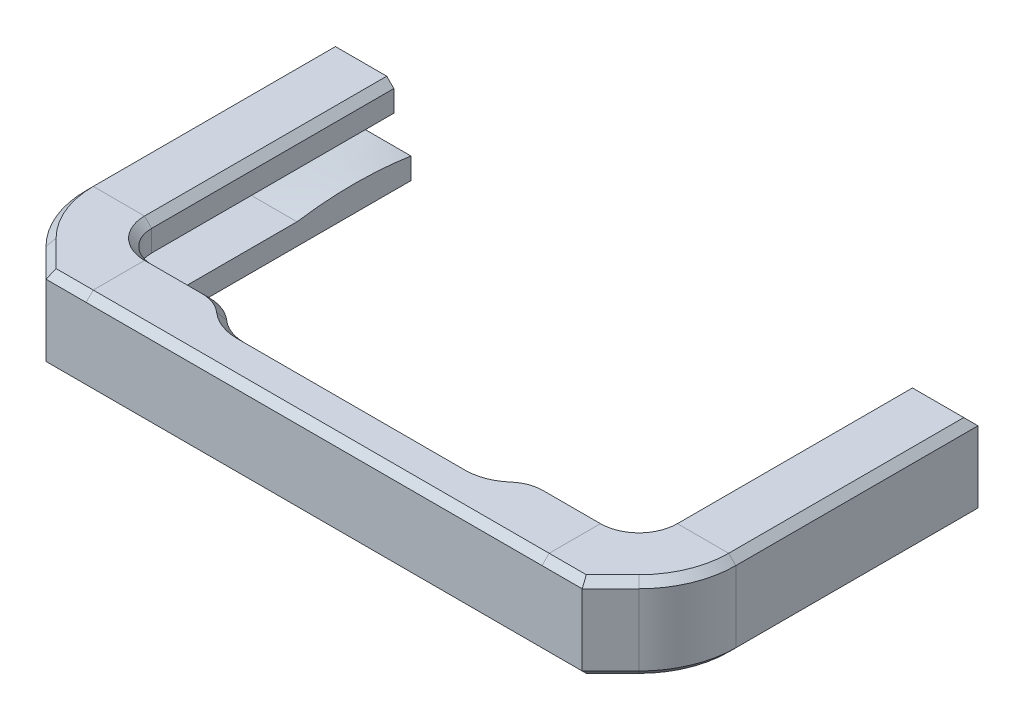
SolidWorks part; units mm, degrees
ref_plane "Front Plane" through (0, 0, 0) normal (0, 0, 1) x (1, 0, 0)
ref_plane "Top Plane" through (0, 0, 0) normal (0, 1, 0) x (1, 0, 0)
ref_plane "Right Plane" through (0, 0, 0) normal (1, 0, 0) x (0, 0, -1)
sketch "Sketch1" plane through (0, 0, 0) normal (0, 1, 0) x (1, 0, 0)
  line L0 (-16, 0) -> (16, 0)
  line L5 (-20, 4) -> (-20, 21)
  line L6 (20, 4) -> (20, 21)
  line L7 (-20, 21) -> (20, 21) construction
  arc A0 (16, 0) -> (20, 4) centre (16, 4) ccw
  arc A1 (-16, 0) -> (-20, 4) centre (-16, 4) cw
  point P8 (20, 0)
  point P11 (-20, 0)
  dimension "D3" = 4
  dimension "D1" = 21
  dimension "D2" = 40
ref_plane "Plane1" through (0, 0, -21) normal (0, 0, 1) x (1, 0, 0)
sketch "Sketch2" plane through (0, 0, -21) normal (0, 0, 1) x (1, 0, 0)
  line L0 (18.2, 1) -> (18.2, 3)
  line L1 (18.2, 3) -> (22.8, 3)
  line L2 (22.8, 3) -> (22.8, -3)
  line L3 (22.8, -3) -> (17, -3)
  line L5 (17, -1) -> (20.8, -1)
  line L6 (20.8, -1) -> (20.8, 1)
  line L7 (20.8, 1) -> (18.2, 1)
  line L8 (20, -1) -> (20, 1) construction
  line L10 (17, -1) -> (17, -3)
  point P10 (20.8, 0)
  point P12 (20, 0)
  dimension "D1" = 2
  dimension "D2" = 0.8
  dimension "D3" = 2
  dimension "D4" = 2
  dimension "D5" = 1.2
  dimension "D6" = 1.8
sweep "Sweep3" add profiles "Sketch2" path "Sketch1"
sketch "Sketch5" plane through (0, -3, 0) normal (0, -1, 0) x (1, 0, 0)
  line L0 (-16, 2.8) -> (-18.8167, 2.8)
  line L1 (-18.8167, 2.8) -> (-20.8083, 0.8083)
  line L2 (-20.8083, 0.8083) -> (-16, 2.8)
  arc A1 (-16, 2.8) -> (-22.8, -4) centre (-16, -4) ccw construction
  dimension "D1" = 45
extrude "Boss-Extrude1" add sketch "Sketch5" against normal through all
mirror "Mirror2" about plane through (0, 0, 0) normal (1, 0, 0) of "Boss-Extrude1"
sketch "Sketch6" plane through (0, 3, 0) normal (0, 1, 0) x (1, 0, 0)
  line L0 (-16, 1.8) -> (16, 1.8) construction
  line L1 (-8, 0.3) -> (8, 0.3)
  line L2 (-11.9686, 1.8) -> (11.9686, 1.8)
  line L3 (0, 0) -> (0, 0.3) construction
  arc A0 (-11.9686, 1.8) -> (-9.9843, 1.05) centre (-11.9686, -1.2) cw
  arc A1 (-9.9843, 1.05) -> (-8, 0.3) centre (-8, 3.3) ccw
  arc A2 (11.9686, 1.8) -> (9.9843, 1.05) centre (11.9686, -1.2) ccw
  arc A3 (9.9843, 1.05) -> (8, 0.3) centre (8, 3.3) cw
  point P14 (0, 0)
  point P16 (10.0342, 1.8)
  point P19 (7.6955, 0.3)
  dimension "D2" = 3
  dimension "D1" = 1.5
  dimension "D3" = 16
extrude "Cut-Extrude1" cut sketch "Sketch6" against normal up to next
chamfer "Chamfer2" distance 0.5 angle 45 34 edges at (13.9843, 3, -1.8) (-10.908, 3, -1.6062) (-9.0607, 3, -0.4938) (0, 3, -0.3) (9.0607, 3, -0.4938) (10.908, 3, -1.6062) (0, -3, -3) (0, -3, 2.8) (0, 3, 2.8) (-13.9843, 3, -1.8) (16.7071, -3, -3.2929) (17.5556, 3, -2.4444) (17, -3, -12.5) (22.8, -3, -12.5) (22.8, 3, -12.5) (18.2, 3, -12.5) (-17, -3, -12.5) (-22.8, -3, -12.5) (-22.8, 3, -12.5) (-18.2, 3, -12.5) (-16.7071, -3, -3.2929) (-22.2824, -3, -1.3978) (-19.8125, 3, 1.8042) (-17.4083, 3, 2.8) (-17.4083, -3, 2.8) (-19.8125, -3, 1.8042) (-22.2824, 3, -1.3978) (-17.5556, 3, -2.4444) (22.2824, 3, -1.3978) (22.2824, -3, -1.3978) (17.4083, -3, 2.8) (19.8125, -3, 1.8042) (19.8125, 3, 1.8042) (17.4083, 3, 2.8)
sketch "Sketch3" plane through (17, 0, 0) normal (-1, 0, 0) x (0, 0, 1)
  line L0 (-4, -1) -> (-21, -1) construction
  line L1 (-21, -1) -> (-13, -1)
  arc A0 (-21, -1) -> (-13, -1) centre (-17, -27.5167) cw
  point P3 (-17, -0.7)
  dimension "D1" = 0.3
  dimension "D2" = 8
sketch "Sketch4" plane through (20.8, 0, 0) normal (-1, 0, 0) x (0, 0, 1)
  line L0 (-21, -1) -> (-13, -1)
  arc A0 (-21, -1) -> (-13, -1) centre (-17, -160.975) cw
  point P5 (-17, -0.95)
  dimension "D1" = 0.05
loft "Loft1" add profiles "Sketch4", "Sketch3"
mirror "Mirror1" about plane through (0, 0, 0) normal (1, 0, 0) of "Loft1"
